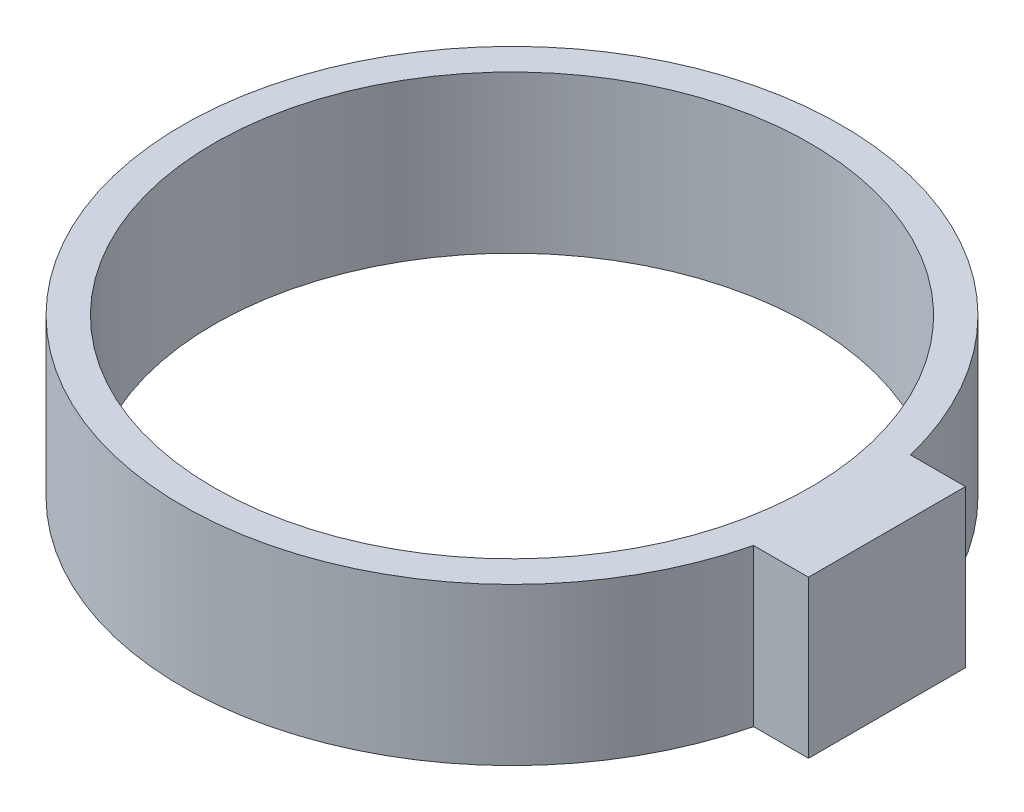
SolidWorks part; units mm, degrees
ref_plane "Front Plane" through (0, 0, 0) normal (0, 0, 1) x (1, 0, 0)
ref_plane "Top Plane" through (0, 0, 0) normal (0, 1, 0) x (1, 0, 0)
ref_plane "Right Plane" through (0, 0, 0) normal (1, 0, 0) x (0, 0, -1)
sketch "Sketch1" plane through (0, 0, 0) normal (0, 1, 0) x (1, 0, 0)
  line L0 (21, 0) -> (54.2576, 0) construction
  line L2 (20.3961, 5) -> (23.8961, 5)
  line L3 (23.8961, 5) -> (23.8961, -5)
  line L4 (23.8961, -5) -> (20.3961, -5)
  circle A0 centre (0, 0) radius 19
  arc A1 (20.3961, 5) -> (20.3961, -5) centre (0, 0) ccw
  circle A2 centre (0, 0) radius 21 construction
  point P10 (19.7285, 0)
  dimension "D1" = 38
  dimension "D3" = 10
  dimension "D4" = 5
  dimension "D5" = 3.5
  dimension "D2" = 2
extrude "Boss-Extrude1" add sketch "Sketch1" along normal blind 10
sketch "Sketch2" plane through (23.8961, 0, 0) normal (1, 0, 0) x (0, 0, -1)
  line L0 (-5, 10) -> (5, 10) construction
  line L1 (5, 0) -> (0, 0)
  line L2 (5, 0) -> (5, 10)
  line L3 (5, 10) -> (0, 10)
  line L4 (0, 0) -> (0, 10)
  dimension "D1" = 5
